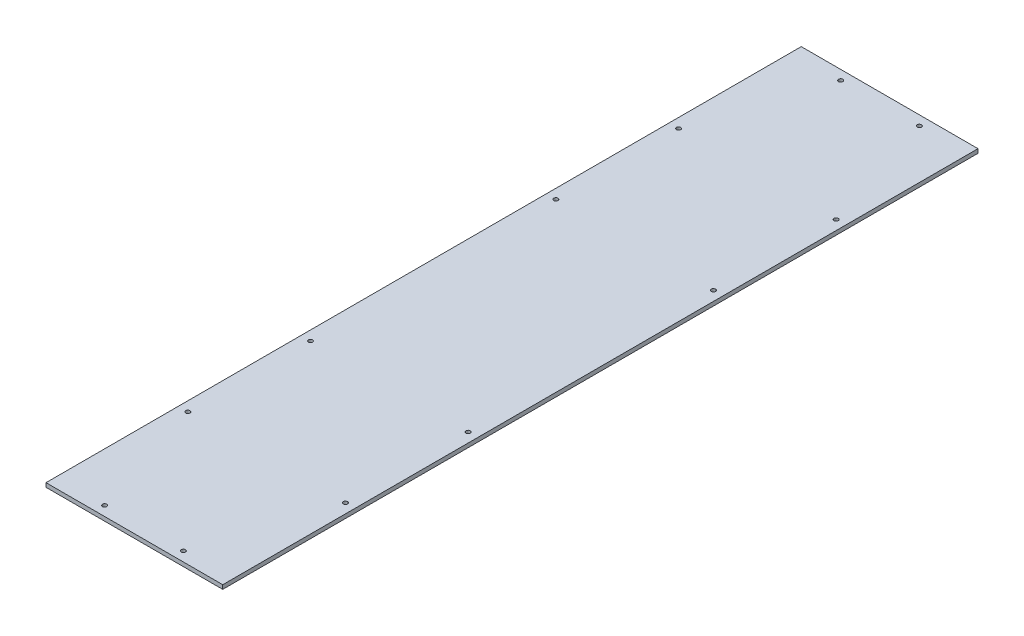
SolidWorks part; units mm, degrees
ref_plane "Front Plane" through (0, 0, 0) normal (0, 0, 1) x (1, 0, 0)
ref_plane "Top Plane" through (0, 0, 0) normal (0, 1, 0) x (1, 0, 0)
ref_plane "Right Plane" through (0, 0, 0) normal (1, 0, 0) x (0, 0, -1)
sketch "Sketch1" plane through (0, 0, 0) normal (0, 1, 0) x (1, 0, 0)
  line L0 (-69.1, 0) -> (69.1, 0) construction
  line L1 (-69.1, 295.275) -> (69.1, 295.275)
  line L2 (-69.1, 295.275) -> (-69.1, -295.275)
  line L3 (-69.1, -295.275) -> (69.1, -295.275)
  line L4 (69.1, 295.275) -> (69.1, -295.275)
  line L5 (-69.1, 295.275) -> (69.1, -295.275) construction
  line L6 (-69.1, -295.275) -> (69.1, 295.275) construction
  line L11 (0, 295.275) -> (0, -295.275) construction
  line L13 (-61.6, 287.775) -> (61.6, 287.775) construction
  line L14 (-61.6, 287.775) -> (-61.6, -287.775) construction
  line L15 (-61.6, -287.775) -> (61.6, -287.775) construction
  line L16 (61.6, 287.775) -> (61.6, -287.775) construction
  line L17 (-61.6, 287.775) -> (61.6, -287.775) construction
  line L18 (-61.6, -287.775) -> (61.6, 287.775) construction
  circle A0 centre (-30.8, 287.775) radius 1.65
  circle A1 centre (-61.6, 191.8483) radius 1.65
  circle A2 centre (-61.6, 95.9217) radius 1.65
  circle A3 centre (61.6, 95.9217) radius 1.65
  circle A4 centre (61.6, 191.8483) radius 1.65
  circle A5 centre (30.8, 287.775) radius 1.65
  circle A6 centre (30.8, -287.775) radius 1.65
  circle A7 centre (61.6, -191.8483) radius 1.65
  circle A8 centre (61.6, -95.9217) radius 1.65
  circle A9 centre (-61.6, -95.9217) radius 1.65
  circle A10 centre (-61.6, -191.8483) radius 1.65
  circle A11 centre (-30.8, -287.775) radius 1.65
  point P0 (0, 0)
  point P6 (0, 0)
  point P11 (0, 0)
  dimension "D5" = 3.3
  dimension "D6" = 3.3
  dimension "D7" = 3.3
  dimension "D3" = 138.2
  dimension "D1" = 7.5
  dimension "D2" = 7.5
  dimension "D4" = 590.55
  dimension "D8" = 30.8
  dimension "D9" = 95.9267
  dimension "D10" = 95.9267
  dimension "D11" = 95.9217
extrude "Boss-Extrude1" add sketch "Sketch1" along normal blind 3.175
equation "\"D6@Sketch1\"=\"D5@Sketch1\""
equation "\"D7@Sketch1\"=\"D6@Sketch1\""
equation "\"D10@Sketch1\"=\"D9@Sketch1\""
